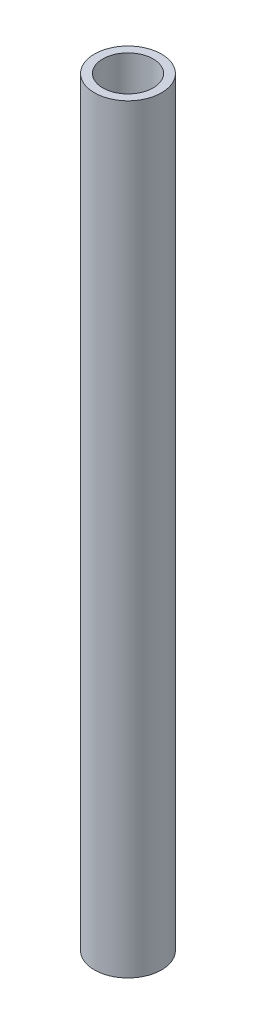
SolidWorks part; units mm, degrees
ref_plane "Front Plane" through (0, 0, 0) normal (0, 0, 1) x (1, 0, 0)
ref_plane "Top Plane" through (0, 0, 0) normal (0, 1, 0) x (1, 0, 0)
ref_plane "Right Plane" through (0, 0, 0) normal (1, 0, 0) x (0, 0, -1)
sketch "Sketch1" plane through (0, 0, 0) normal (0, 1, 0) x (1, 0, 0)
  circle A0 centre (0, 0) radius 3
  circle A1 centre (0, 0) radius 4
extrude "Boss-Extrude1" add sketch "Sketch1" along normal blind 90.5
